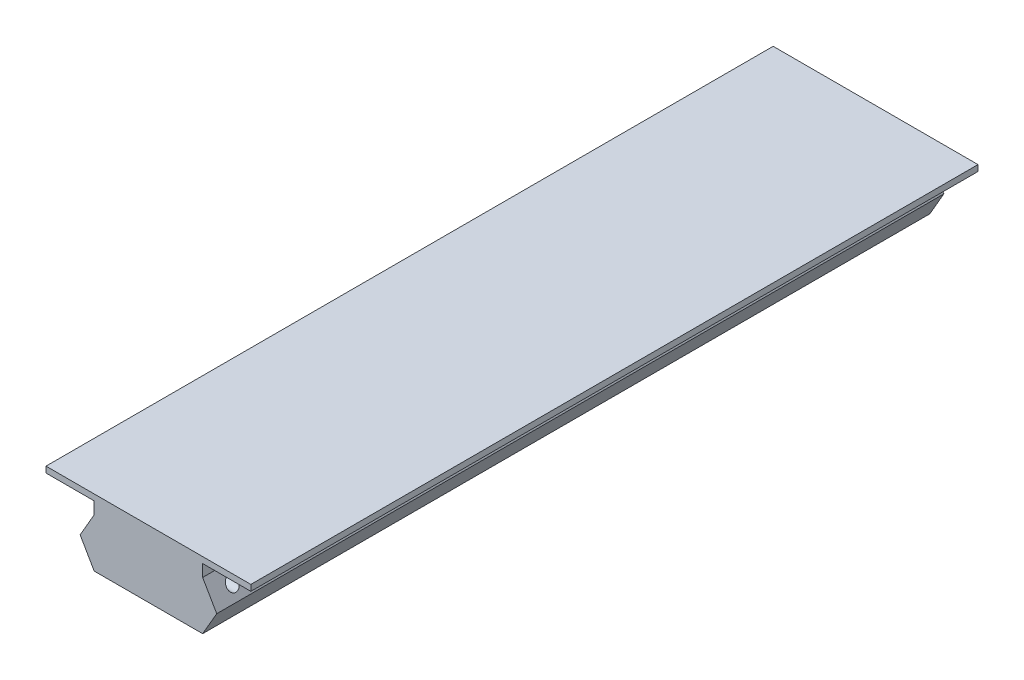
SolidWorks part; units mm, degrees
ref_plane "Front Plane" through (0, 0, 0) normal (0, 0, 1) x (1, 0, 0)
ref_plane "Top Plane" through (0, 0, 0) normal (0, 1, 0) x (1, 0, 0)
ref_plane "Right Plane" through (0, 0, 0) normal (1, 0, 0) x (0, 0, -1)
sketch "Sketch1" plane through (0, 0, 0) normal (0, 0, 1) x (1, 0, 0)
  line L0 (0, 0) -> (9.693, 0) construction
  line L1 (9.693, 0) -> (-8.307, 0)
  line L2 (-8.307, 0) -> (-10.642, 4.0443)
  line L3 (-10.642, 4.0443) -> (-8.307, 8.0887)
  line L5 (9.693, 8.0887) -> (12.028, 4.0443)
  line L6 (12.028, 4.0443) -> (9.693, 0)
  line L7 (-8.307, 8.0887) -> (-8.307, 10.0887)
  line L8 (-8.307, 10.0887) -> (-16.307, 10.0887)
  line L9 (-16.307, 10.0887) -> (-16.307, 11.0887)
  line L10 (-16.307, 11.0887) -> (17.693, 11.0887)
  line L11 (17.693, 11.0887) -> (17.693, 10.0887)
  line L12 (17.693, 10.0887) -> (9.693, 10.0887)
  line L13 (9.693, 10.0887) -> (9.693, 8.0887)
  dimension "D1" = 18
  dimension "D2" = 120
  dimension "D3" = 120
  dimension "D4" = 120
  dimension "D5" = 120
  dimension "D6" = 4.67
  dimension "D7" = 34
  dimension "D8" = 2
  dimension "D9" = 8
extrude "Boss-Extrude1" add sketch "Sketch1" against normal blind 120.69 contours L10 L11 L12 L13 L5 L6 L1 L2 L3 L7 L8 L9
sketch "Sketch2" plane through (0, 0, 0) normal (1, 0, 0) x (0, 0, -1)
  line L0 (120.69, 8.0887) -> (0, 8.0887) construction
  line L1 (0, 55) -> (0, -55) construction
  circle A0 centre (3.71, 5.9887) radius 1
  dimension "D1" = 2
  dimension "D2" = 2.1
  dimension "D3" = 3.71
extrude "Cut-Extrude1" cut sketch "Sketch2" against normal through all both and the other way through all
sketch "Sketch3" plane through (0, 0, 0) normal (1, 0, 0) x (0, 0, -1)
  line L0 (-5.5306, 10.7632) -> (49994.4694, 10.7632) construction
pattern_linear "LPattern1" count 32 spacing 3.71 along (0, 0, -1) of "Cut-Extrude1"
